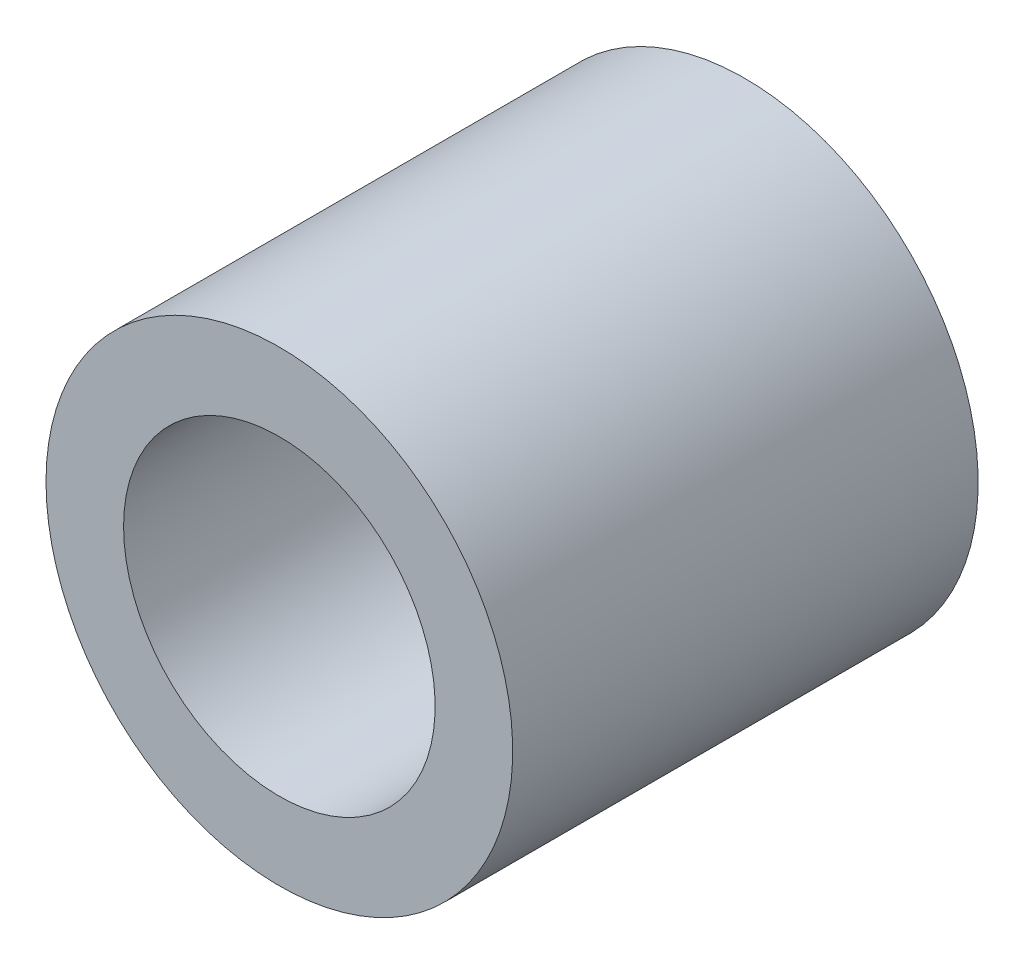
SolidWorks part; units mm, degrees
ref_plane "Front Plane" through (0, 0, 0) normal (0, 0, 1) x (1, 0, 0)
ref_plane "Top Plane" through (0, 0, 0) normal (0, 1, 0) x (1, 0, 0)
ref_plane "Right Plane" through (0, 0, 0) normal (1, 0, 0) x (0, 0, -1)
sketch "Sketch1" plane through (0, 0, 0) normal (0, 0, 1) x (1, 0, 0)
  circle A0 centre (0, 0) radius 4.7752
  circle A1 centre (0, 0) radius 3.1877
  dimension "OD" = 9.5504
  dimension "ID" = 6.3754
sketch "Sketch2" plane through (0, 0, 0) normal (1, 0, 0) x (0, 0, -1)
  line L2 (4.7625, 0) -> (-4.7625, 0) construction
  line L4 (-4.7625, -4.7752) -> (-4.7625, 4.7752) construction
  line L5 (-4.7625, -3.1877) -> (4.7625, -3.1877)
  line L6 (4.7625, 3.1877) -> (-4.7625, 3.1877)
  line L7 (4.7625, -4.7752) -> (4.7625, 4.7752) construction
  line L8 (-4.7625, 4.7752) -> (4.7625, 4.7752) construction
  line L9 (-4.7625, -4.7752) -> (4.7625, -4.7752) construction
  line L10 (0, 4.7752) -> (0, -4.7752) construction
  line L11 (0, 3.1877) -> (0, -3.1877) construction
  point P4 (0, -3.1877)
  point P7 (0, 3.1877)
  point P8 (0, 0)
  point P12 (-4.7625, 0)
  point P15 (4.7625, 0)
  point P16 (0, -4.7752)
  point P17 (0, 4.7752)
  dimension "Length" = 9.525
sketch "Sketch5" plane through (0, 0, 0) normal (0, 0, 1) x (1, 0, 0)
  circle A1 centre (0, 0) radius 3.1877
  circle A2 centre (0, 0) radius 3.1877
  circle A3 centre (0, 0) radius 4.7752
  circle A4 centre (0, 0) radius 4.7752
  dimension "D1" = 0
  dimension "D2" = 0
extrude "Boss-Extrude1" add sketch "Sketch5" along normal up to vertex (4.7625 mm away) and the other way up to vertex (4.7625 mm away) up to point (0, 0, 4.7625) other way up to point (0, 0, -4.7625)
sketch "Sketch4" plane through (0, 0, 4.7625) normal (0, 0, 1) x (1, 0, 0)
  line L0 (0, 0) -> (-2.254, 2.254)
  line L2 (0, -4.7752) -> (0, 4.7752) construction
  circle A1 centre (0, 0) radius 3.1877 construction
  dimension "D1" = 45
equation "\"D1\"= \"Length@Sketch2\""
